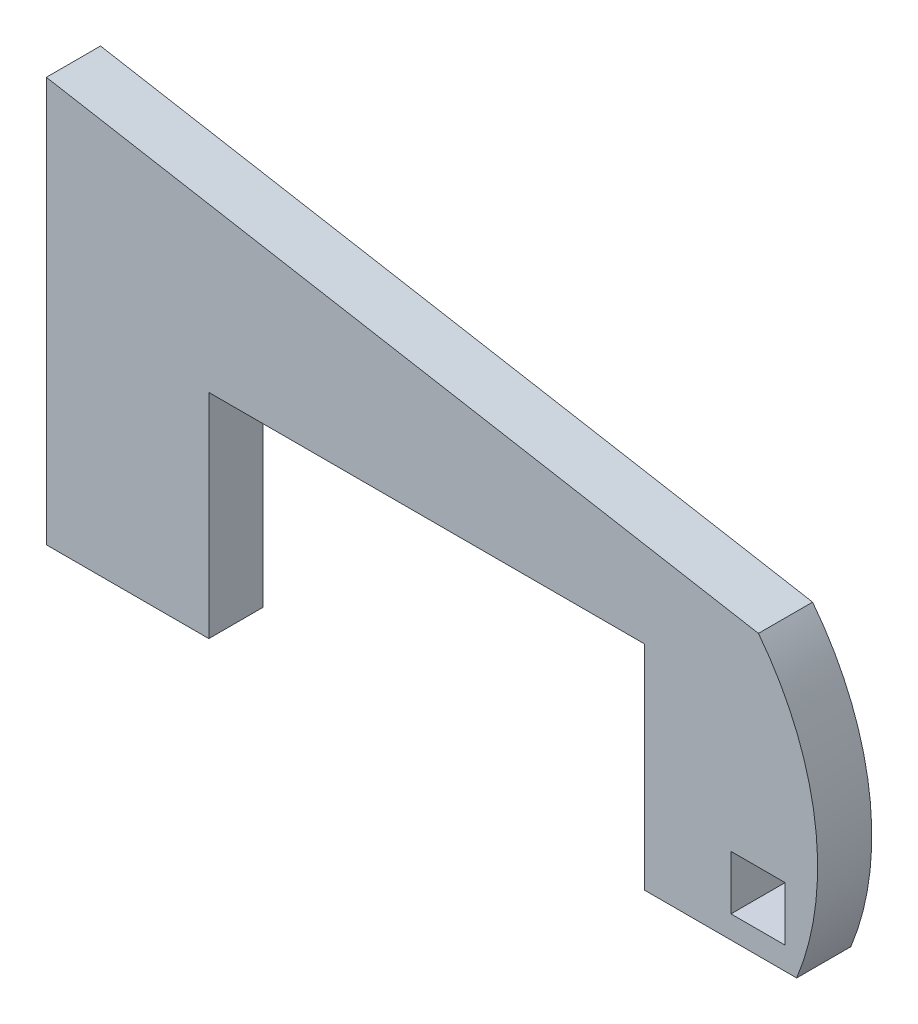
SolidWorks part; units mm, degrees
material "Balsa"
ref_plane "Plan de face" through (0, 0, 0) normal (0, 0, 1) x (1, 0, 0)
ref_plane "Plan de dessus" through (0, 0, 0) normal (0, 1, 0) x (1, 0, 0)
ref_plane "Plan de droite" through (0, 0, 0) normal (1, 0, 0) x (0, 0, -1)
sketch "Esquisse1" plane through (0, 0, 0) normal (0, 0, 1) x (1, 0, 0)
  line L0 (0, 0) -> (0, -19.685)
  line L1 (0, -19.685) -> (20, -19.685)
  line L2 (20, -19.685) -> (20, 4.4334)
  line L3 (20, 4.4334) -> (-55.2, 17.6932)
  line L4 (-55.2, 17.6932) -> (-55.2, -19.685)
  line L6 (-55.2, -19.685) -> (-40.2, -19.685)
  line L7 (-40.2, -19.685) -> (-40.2, 0)
  line L8 (-40.2, 0) -> (0, 0)
  dimension "D1" = 19.685
  dimension "D2" = 40.2
  dimension "D3" = 19.685
  dimension "D4" = 20
  dimension "D5" = 15
  dimension "D6" = 37.3782
  dimension "D7" = 100
extrude "Boss.-Extru.1" add sketch "Esquisse1" along normal blind 5 contours L3 L4 L6 L7 L8 L0 L1 L2
sketch "Esquisse2" plane through (0, 0, 0) normal (0, 0, -1) x (-1, 0, 0)
  line L0 (0, -19.685) -> (-20, -19.685) construction
  line L1 (-20, 4.4334) -> (55.2, 17.6932) construction
  line L2 (-10.5372, 6.1019) -> (-11.2331, 10.049)
  line L3 (-11.2331, 10.049) -> (-30.7322, 6.6108)
  line L4 (-30.7322, 6.6108) -> (-25.7328, -21.7423)
  line L5 (-25.7328, -21.7423) -> (-14.065, -19.685)
  line L7 (-13, -17.5925) -> (-13, -12.5925)
  line L8 (-20, -19.685) -> (-20, 4.4334) construction
  line L9 (-13, -17.5925) -> (-8, -17.5925)
  line L10 (-8, -12.5925) -> (-8, -17.5925)
  line L12 (-13, -12.5925) -> (-8, -12.5925)
  arc A1 (-14.065, -19.685) -> (-10.5372, 6.1019) centre (10, -9.8425) cw
  dimension "D4" = 26
  dimension "D1" = 5
  dimension "D2" = 2.0925
  dimension "D3" = 12
  dimension "D5" = 5
extrude "Enlèv. mat.-Extru.1" cut sketch "Esquisse2" against normal blind 5
